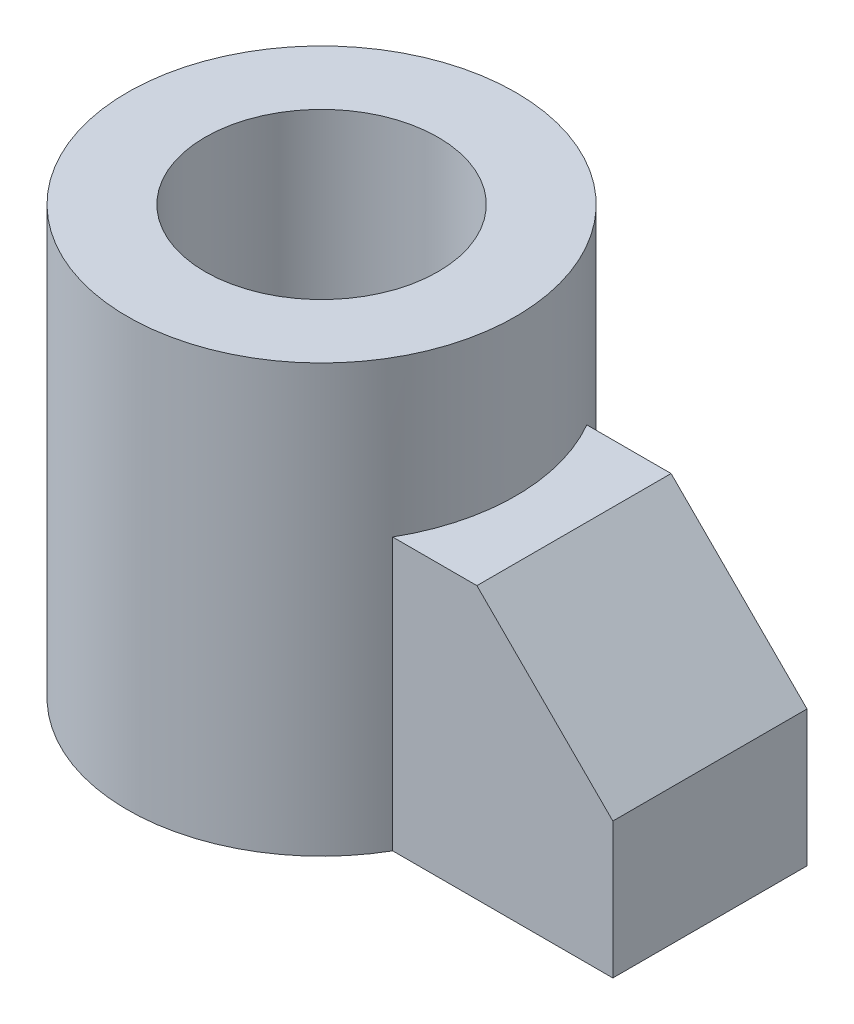
SolidWorks part; units mm, degrees
ref_plane "Front Plane" through (0, 0, 0) normal (0, 0, 1) x (1, 0, 0)
ref_plane "Top Plane" through (0, 0, 0) normal (0, 1, 0) x (1, 0, 0)
ref_plane "Right Plane" through (0, 0, 0) normal (1, 0, 0) x (0, 0, -1)
sketch "Sketch1" plane through (0, 0, 0) normal (0, 1, 0) x (1, 0, 0)
  line L1 (0, 0) -> (127, 0)
  line L2 (0, 0) -> (0, 63.5)
  line L3 (0, 63.5) -> (127, 63.5)
  line L4 (127, 0) -> (127, 63.5)
  dimension "D1" = 63.5
  dimension "D2" = 127
extrude "Boss-Extrude1" add sketch "Sketch1" along normal blind 88.9
sketch "Sketch3" plane through (0, 0, 0) normal (0, -1, 0) x (1, 0, 0)
  line L0 (0, -63.5) -> (0, 0) construction
  circle A0 centre (0, -31.75) radius 63.5
  dimension "D1" = 127
extrude "Boss-Extrude2" add sketch "Sketch3" against normal blind 139.7
sketch "Sketch4" plane through (0, 0, 0) normal (0, 0, 1) x (1, 0, 0)
  line L0 (82.55, 88.9) -> (127, 44.45)
  line L1 (54.9926, 88.9) -> (127, 88.9) construction
  line L2 (127, 88.9) -> (127, 0) construction
  line L4 (82.55, 88.9) -> (127, 88.9)
  line L7 (127, 88.9) -> (127, 44.45)
  dimension "D1" = 45
  dimension "D2" = 44.45
extrude "Cut-Extrude1" cut sketch "Sketch4" against normal up to next
sketch "Sketch5" plane through (0, 139.7, 0) normal (0, 1, 0) x (1, 0, 0)
  circle A0 centre (0, 31.75) radius 38.1
  circle A1 centre (0, 31.75) radius 63.5 construction
  dimension "D1" = 76.2
  dimension "D2" = 0
extrude "Cut-Extrude2" cut sketch "Sketch5" against normal up to next
